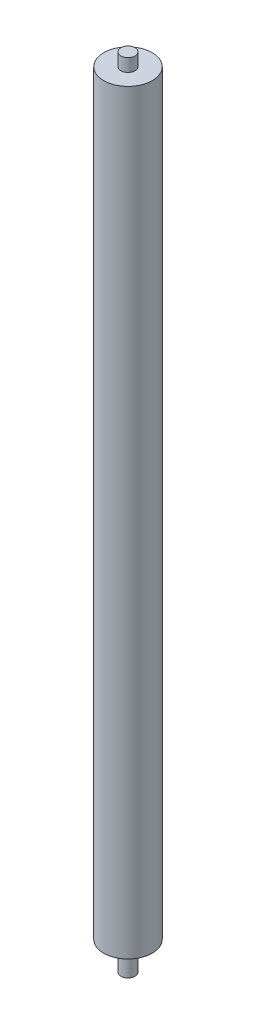
SolidWorks part; units mm, degrees
ref_plane "Front Plane" through (0, 0, 0) normal (0, 0, 1) x (1, 0, 0)
ref_plane "Top Plane" through (0, 0, 0) normal (0, 1, 0) x (1, 0, 0)
ref_plane "Right Plane" through (0, 0, 0) normal (1, 0, 0) x (0, 0, -1)
sketch "Sketch1" plane through (0, 0, 0) normal (0, 1, 0) x (1, 0, 0)
  circle A0 centre (0, 0) radius 10
extrude "Boss-Extrude1" add sketch "Sketch1" along normal blind 40
sketch "Sketch2" plane through (0, 40, 0) normal (0, 1, 0) x (1, 0, 0)
  circle A0 centre (0, 0) radius 34
extrude "Boss-Extrude2" add sketch "Sketch2" along normal blind 1060
sketch "Sketch3" plane through (0, 1100, 0) normal (0, 1, 0) x (1, 0, 0)
  circle A0 centre (0, 0) radius 10
extrude "Boss-Extrude3" add sketch "Sketch3" along normal blind 18
